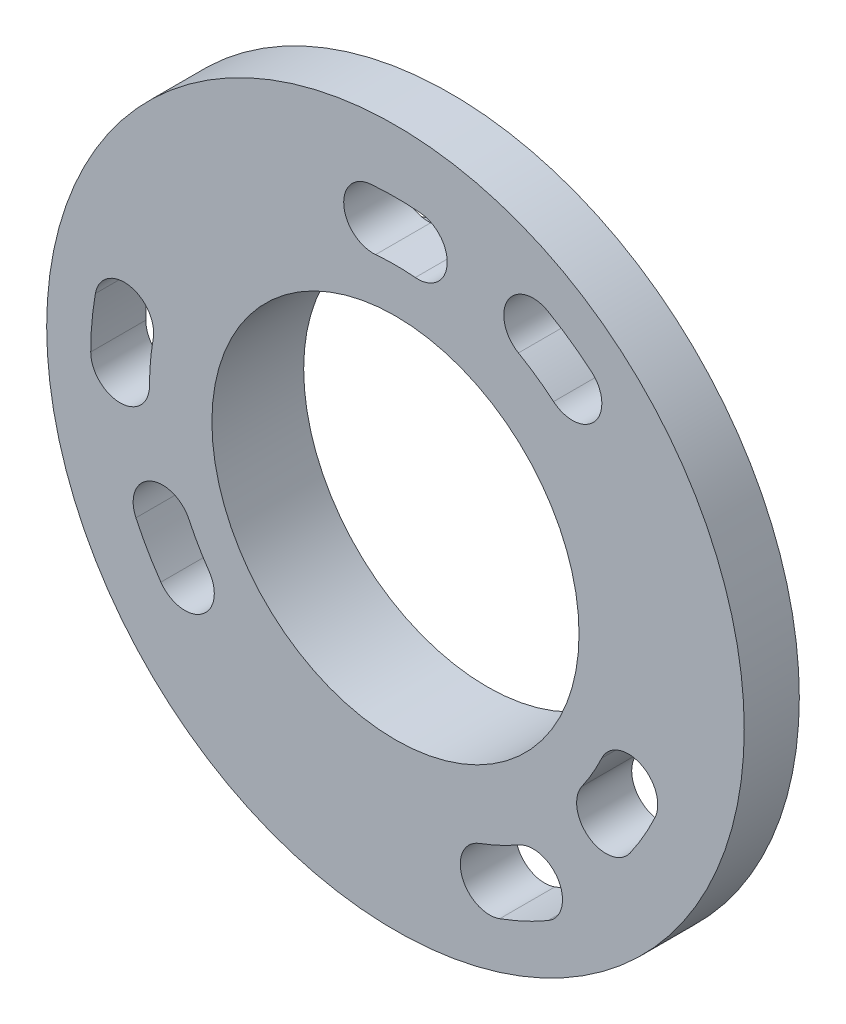
SolidWorks part; units mm, degrees
ref_plane "Front Plane" through (0, 0, 0) normal (0, 0, 1) x (1, 0, 0)
ref_plane "Top Plane" through (0, 0, 0) normal (0, 1, 0) x (1, 0, 0)
ref_plane "Right Plane" through (0, 0, 0) normal (1, 0, 0) x (0, 0, -1)
sketch "Sketch1" plane through (0, 0, 0) normal (0, 0, 1) x (1, 0, 0)
  line L0 (0, 14) -> (0, 0) construction
  line L1 (0, 0) -> (8.6036, 12.2873) construction
  line L2 (-1.2202, 13.9467) -> (0, 0) construction
  line L3 (0, 0) -> (1.2202, 13.9467) construction
  line L4 (7.5, 12.9904) -> (0, 0) construction
  circle A0 centre (0, 0) radius 19
  circle A1 centre (0, 0) radius 10
  circle A2 centre (0, 0) radius 15 construction
  circle A3 centre (0, 0) radius 14 construction
  arc A4 (-1.2202, 13.9467) -> (1.2202, 13.9467) centre (0, 0) cw construction
  arc A5 (1.3596, 15.5406) -> (-1.3596, 15.5406) centre (0, 0) ccw
  arc A6 (1.0807, 12.3528) -> (-1.0807, 12.3528) centre (0, 0) ccw
  arc A7 (1.0807, 12.3528) -> (1.3596, 15.5406) centre (1.2202, 13.9467) ccw
  arc A8 (-1.3596, 15.5406) -> (-1.0807, 12.3528) centre (-1.2202, 13.9467) ccw
  arc A9 (7.5, 12.9904) -> (9.6418, 11.4907) centre (0, 0) cw construction
  arc A10 (10.6703, 12.7163) -> (8.3, 14.376) centre (0, 0) ccw
  arc A11 (8.6134, 10.265) -> (6.7, 11.6047) centre (0, 0) ccw
  arc A12 (8.6134, 10.265) -> (10.6703, 12.7163) centre (9.6418, 11.4907) ccw
  arc A13 (8.3, 14.376) -> (6.7, 11.6047) centre (7.5, 12.9904) ccw
  arc A14 (12.6883, -5.9167) -> (11.4681, -8.0301) centre (0, 0) cw construction
  arc A15 (12.7788, -8.9478) -> (14.1384, -6.5928) centre (0, 0) ccw
  arc A16 (10.1575, -7.1123) -> (11.2382, -5.2405) centre (0, 0) ccw
  arc A17 (10.1575, -7.1123) -> (12.7788, -8.9478) centre (11.4681, -8.0301) ccw
  arc A18 (14.1384, -6.5928) -> (11.2382, -5.2405) centre (12.6883, -5.9167) ccw
  arc A19 (7.5, -12.9904) -> (5.1303, -14.0954) centre (0, 0) cw construction
  arc A20 (5.6775, -15.5989) -> (8.3, -14.376) centre (0, 0) ccw
  arc A21 (4.5831, -12.5919) -> (6.7, -11.6047) centre (0, 0) ccw
  arc A22 (4.5831, -12.5919) -> (5.6775, -15.5989) centre (5.1303, -14.0954) ccw
  arc A23 (8.3, -14.376) -> (6.7, -11.6047) centre (7.5, -12.9904) ccw
  arc A24 (-11.4681, -8.0301) -> (-12.6883, -5.9167) centre (0, 0) cw construction
  arc A25 (-14.1384, -6.5928) -> (-12.7788, -8.9478) centre (0, 0) ccw
  arc A26 (-11.2382, -5.2405) -> (-10.1575, -7.1123) centre (0, 0) ccw
  arc A27 (-11.2382, -5.2405) -> (-14.1384, -6.5928) centre (-12.6883, -5.9167) ccw
  arc A28 (-12.7788, -8.9478) -> (-10.1575, -7.1123) centre (-11.4681, -8.0301) ccw
  arc A29 (-15, 0) -> (-14.7721, 2.6047) centre (0, 0) cw construction
  arc A30 (-16.3478, 2.8826) -> (-16.6, 0) centre (0, 0) ccw
  arc A31 (-13.1964, 2.3269) -> (-13.4, 0) centre (0, 0) ccw
  arc A32 (-13.1964, 2.3269) -> (-16.3478, 2.8826) centre (-14.7721, 2.6047) ccw
  arc A33 (-16.6, 0) -> (-13.4, 0) centre (-15, 0) ccw
  point P6 (0, 14)
  point P7 (8.6036, 12.2873)
  point P10 (12.1244, -7)
  point P12 (6.3393, -13.5946)
  point P15 (-12.1244, -7)
  point P16 (-14.9429, 1.3073)
  point P17 (0, 0)
  point P18 (0, 14)
  point P27 (8.6036, 12.2873)
  point P36 (12.1244, -7)
  point P37 (6.3393, -13.5946)
  point P40 (12.1244, -7)
  point P47 (6.3393, -13.5946)
  point P52 (-12.1244, -7)
  point P53 (-14.9429, 1.3073)
  point P56 (-12.1244, -7)
  point P63 (-14.9429, 1.3073)
  point P68 (0, 0)
  dimension "D1" = 38
  dimension "D2" = 20
  dimension "D3" = 30
  dimension "D4" = 28
  dimension "D9" = 3.2
  dimension "D10" = 3.2
  dimension "D5" = 35
  dimension "D6" = 3
  dimension "D7" = 5
  dimension "D8" = 5
  dimension "D11" = 5
  dimension "D12" = 3
extrude "Boss-Extrude1" add sketch "Sketch1" along normal blind 3
sketch "Sketch2" plane through (0, 0, 0) normal (0, 0, -1) x (-1, 0, 0)
  circle A0 centre (0, 0) radius 11
  circle A1 centre (0, 0) radius 10 construction
  circle A2 centre (0, 0) radius 10
  dimension "D1" = 22
extrude "Boss-Extrude2" add sketch "Sketch2" along normal blind 2
